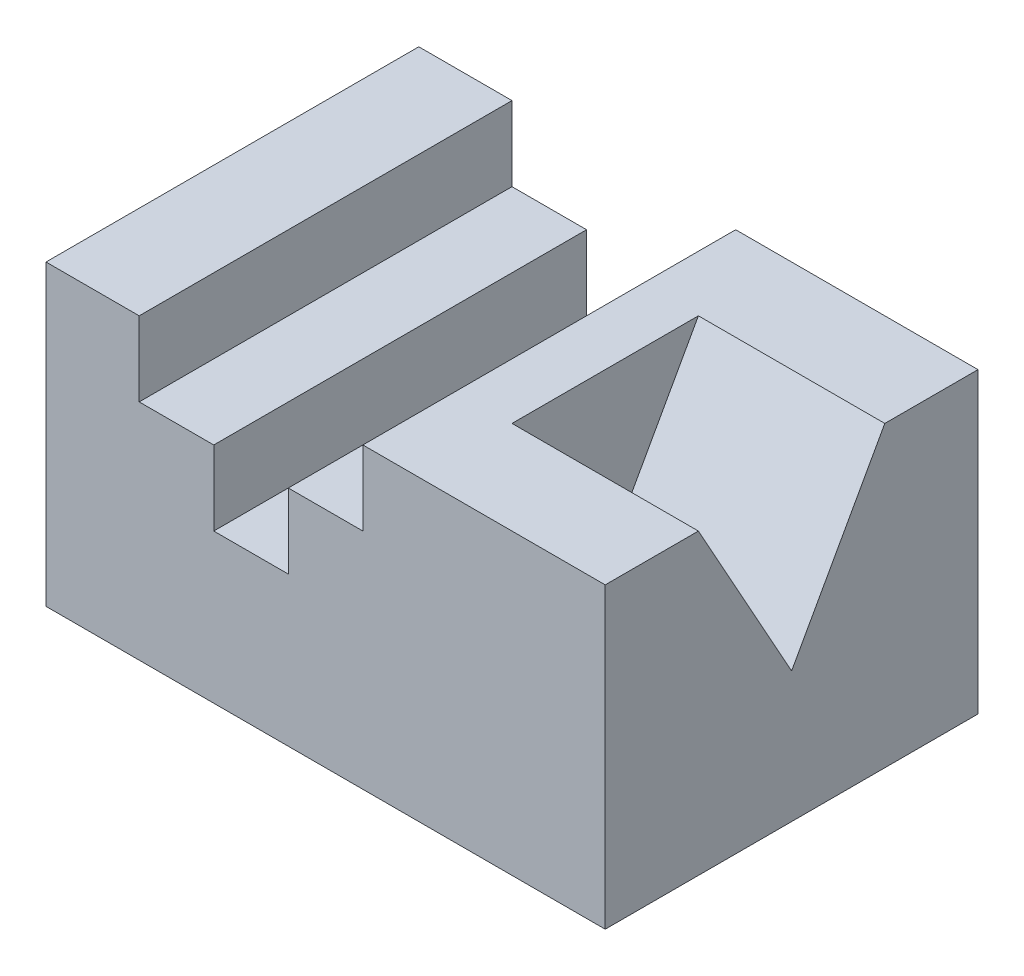
SolidWorks part; units mm, degrees
ref_plane "Front Plane" through (0, 0, 0) normal (0, 0, 1) x (1, 0, 0)
ref_plane "Top Plane" through (0, 0, 0) normal (0, 1, 0) x (1, 0, 0)
ref_plane "Right Plane" through (0, 0, 0) normal (1, 0, 0) x (0, 0, -1)
sketch "Sketch1" plane through (0, 0, 0) normal (0, 0, 1) x (1, 0, 0)
  line L0 (0, 0) -> (0, 80)
  line L1 (0, 80) -> (25, 80)
  line L2 (25, 80) -> (25, 60)
  line L3 (25, 60) -> (45, 60)
  line L4 (45, 60) -> (45, 40)
  line L5 (45, 40) -> (65, 40)
  line L6 (65, 40) -> (65, 60)
  line L7 (65, 60) -> (85, 60)
  line L8 (85, 60) -> (85, 80)
  line L9 (85, 80) -> (150, 80)
  line L10 (150, 80) -> (150, 0)
  line L11 (150, 0) -> (0, 0)
  dimension "D1" = 80
  dimension "D2" = 150
  dimension "D3" = 25
  dimension "D6" = 20
  dimension "D7" = 20
  dimension "D8" = 20
extrude "Boss-Extrude1" add sketch "Sketch1" against normal blind 100
sketch "Sketch2" plane through (150, 0, 0) normal (1, 0, 0) x (0, 0, -1)
  line L0 (100, 0) -> (100, 80) construction
  line L1 (100, 80) -> (0, 80) construction
  line L2 (25, 80) -> (50, 35)
  line L3 (50, 35) -> (75, 80)
  line L5 (0, 0) -> (0, 80) construction
  point P0 (25, 80)
  dimension "D1" = 25
  dimension "D2" = 25
  dimension "D3" = 45
  dimension "D4" = 50
extrude "Cut-Extrude2" cut sketch "Sketch2" against normal blind 50 and the other way through all contours L2 L3
